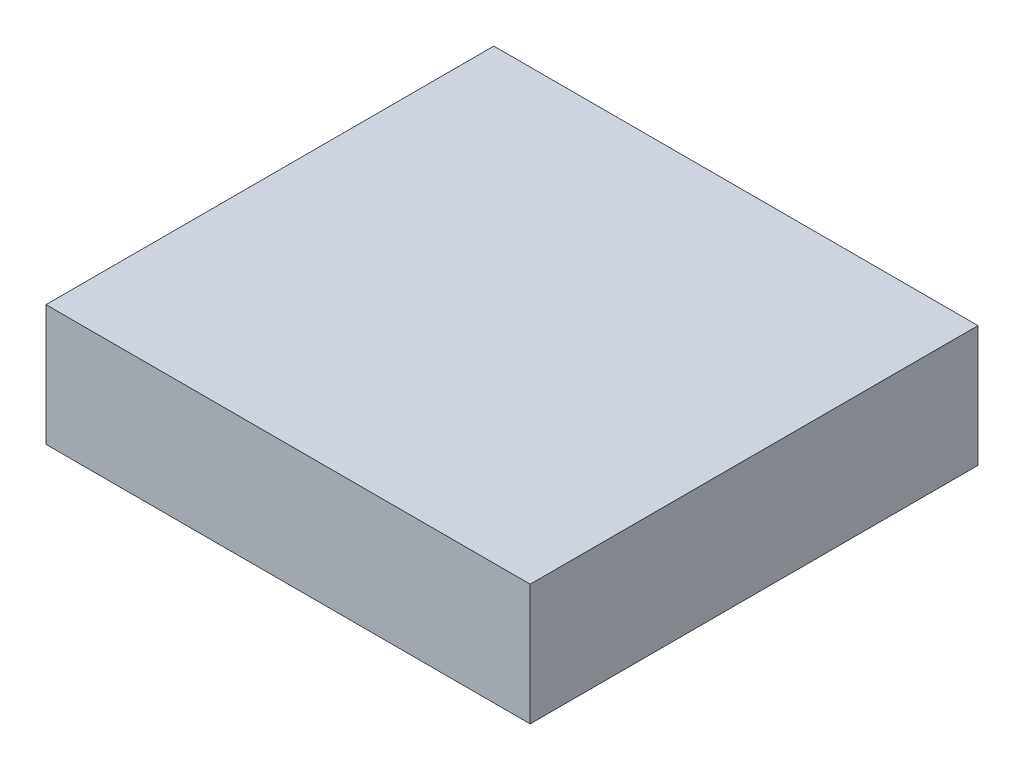
SolidWorks part; units mm, degrees
ref_plane "Front Plane" through (0, 0, 0) normal (0, 0, 1) x (1, 0, 0)
ref_plane "Top Plane" through (0, 0, 0) normal (0, 1, 0) x (1, 0, 0)
ref_plane "Right Plane" through (0, 0, 0) normal (1, 0, 0) x (0, 0, -1)
sketch "Sketch1" plane through (0, 0, 0) normal (0, 1, 0) x (1, 0, 0)
  line L1 (0, 0) -> (40, 0)
  line L2 (0, 0) -> (0, 37)
  line L3 (0, 37) -> (40, 37)
  line L4 (40, 0) -> (40, 37)
extrude "Boss-Extrude1" add sketch "Sketch1" against normal blind 10
